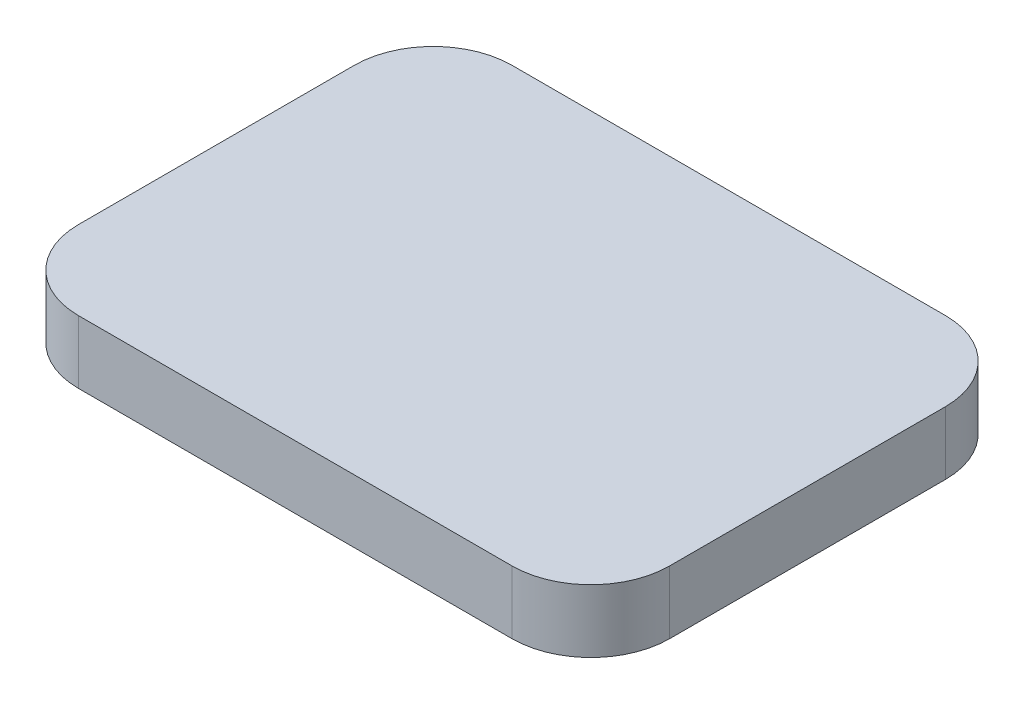
SolidWorks part; units mm, degrees
ref_plane "Front" through (0, 0, 0) normal (0, 0, 1) x (1, 0, 0)
ref_plane "Top" through (0, 0, 0) normal (0, 1, 0) x (1, 0, 0)
ref_plane "Right" through (0, 0, 0) normal (1, 0, 0) x (0, 0, -1)
sketch "Эскиз1" plane through (0, 0, 0) normal (0, 1, 0) x (1, 0, 0)
  line L1 (-7.5, 5.5) -> (7.5, 5.5)
  line L2 (-7.5, 5.5) -> (-7.5, -5.5)
  line L3 (-7.5, -5.5) -> (7.5, -5.5)
  line L4 (7.5, 5.5) -> (7.5, -5.5)
  line L5 (-7.5, 5.5) -> (7.5, -5.5) construction
  line L6 (-7.5, -5.5) -> (7.5, 5.5) construction
  point P0 (0, 0)
  dimension "D1" = 11
  dimension "D2" = 15
extrude "База" add sketch "Эскиз1" along normal blind 1.6
fillet "Скругление1" radius 2 4 edges at (-7.5, 0.8, -5.5) (7.5, 0.8, -5.5) (-7.5, 0.8, 5.5) (7.5, 0.8, 5.5)
